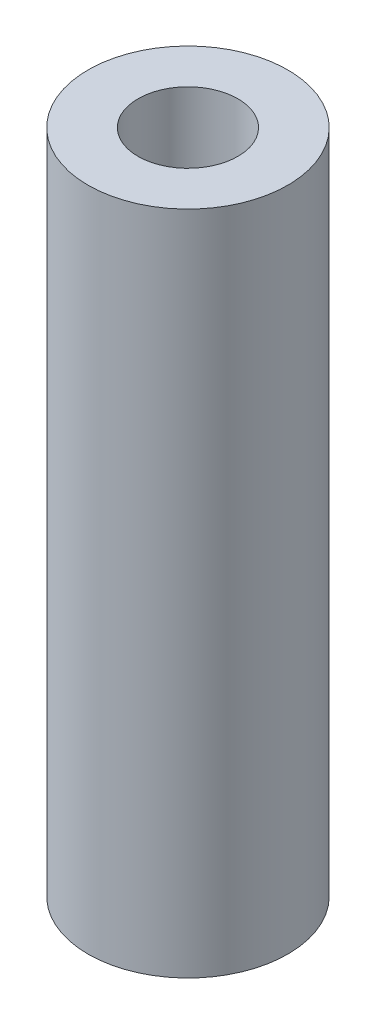
SolidWorks part; units mm, degrees
ref_plane "Front Plane" through (0, 0, 0) normal (0, 0, 1) x (1, 0, 0)
ref_plane "Top Plane" through (0, 0, 0) normal (0, 1, 0) x (1, 0, 0)
ref_plane "Right Plane" through (0, 0, 0) normal (1, 0, 0) x (0, 0, -1)
sketch "Sketch1" plane through (0, 0, 0) normal (0, 1, 0) x (1, 0, 0)
  circle A0 centre (0, 0) radius 3
  circle A1 centre (0, 0) radius 1.5
extrude "Boss-Extrude1" add sketch "Sketch1" along normal blind 20
